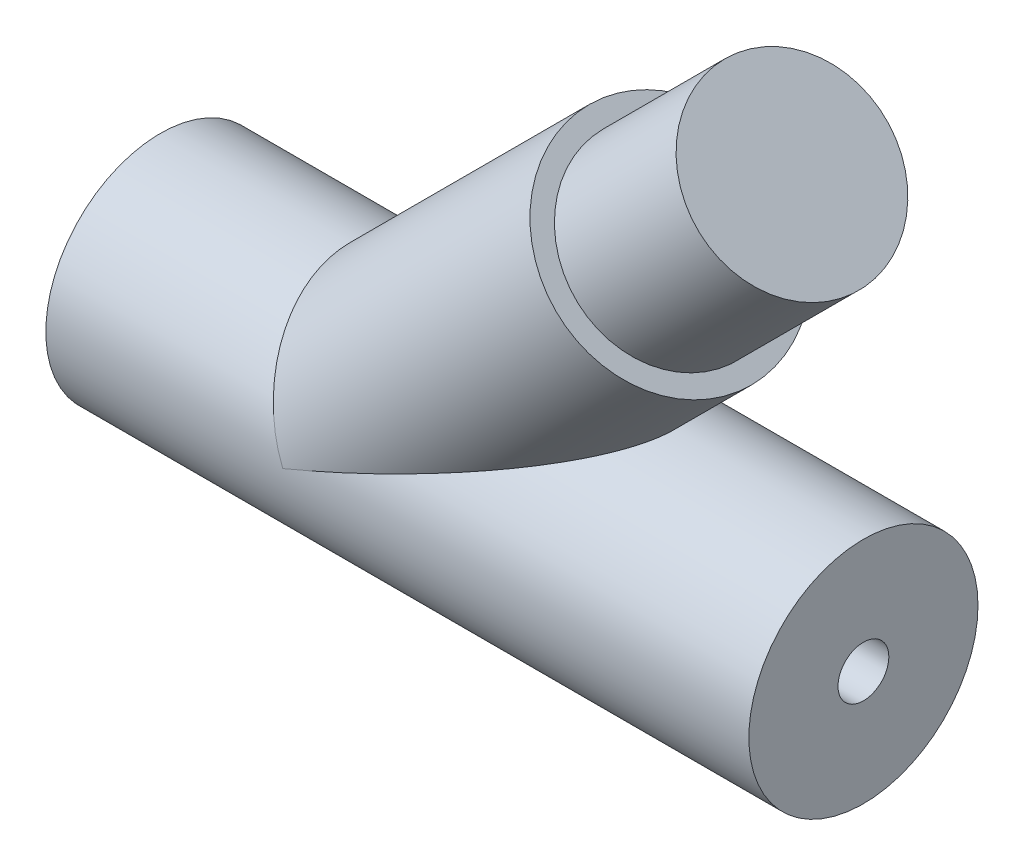
SolidWorks part; units mm, degrees
ref_plane "Front Plane" through (0, 0, 0) normal (0, 0, 1) x (1, 0, 0)
ref_plane "Top Plane" through (0, 0, 0) normal (0, 1, 0) x (1, 0, 0)
ref_plane "Right Plane" through (0, 0, 0) normal (1, 0, 0) x (0, 0, -1)
sketch "Sketch1" plane through (0, 0, 0) normal (1, 0, 0) x (0, 0, -1)
  circle A0 centre (0, 0) radius 28.194
  dimension "D1" = 56.388
extrude "Boss-Extrude1" add sketch "Sketch1" along normal blind 173
sketch "Sketch4" plane through (0, 0, 0) normal (0, 1, 0) x (1, 0, 0)
  line L0 (58.3, -34.1123) -> (58.3, 43.0803)
  line L1 (0, 28.194) -> (0, -28.194) construction
  circle A0 centre (58.3, 0) radius 15
  dimension "D1" = 58.3
ref_plane "Plane1" through (29.15, 29.15, 0) normal (0.7071, 0.7071, 0) x (0.7071, -0.7071, 0)
sketch "Sketch5" plane through (29.15, 29.15, 0) normal (0.7071, 0.7071, 0) x (0.7071, -0.7071, 0)
  circle A0 centre (41.2243, 0) radius 28.194
  dimension "D1" = 56.388
extrude "Boss-Extrude3" add sketch "Sketch5" along normal blind 95 contours A0
sketch "Sketch7" plane through (0, 0, 0) normal (-1, 0, 0) x (0, 0, 1)
  circle A0 centre (0, 0) radius 6.25
  dimension "D1" = 12.5
extrude "Cut-Extrude1" cut sketch "Sketch7" against normal blind 369.4
scale "Scale2" bodies to scale 107 scale about centroid uniform scaling yes scale factor 0.6
sketch "Sketch9" plane through (78.3509, 78.3509, 0) normal (0.7071, 0.7071, 0) x (0, 0, -1)
  circle A0 centre (0.0001, -46.6866) radius 13.97
  dimension "D1" = 27.94
extrude "Boss-Extrude4" add sketch "Sketch9" along normal blind 25.4
